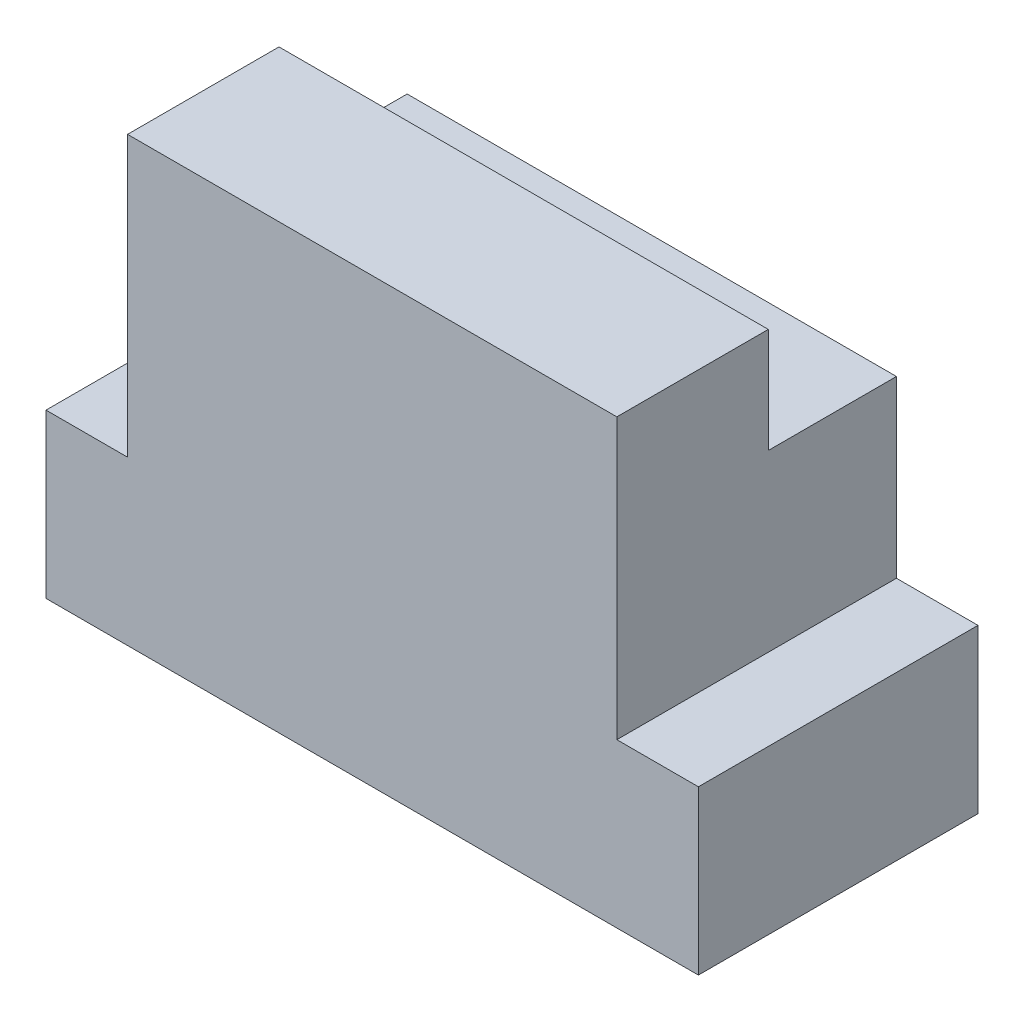
SolidWorks part; units mm, degrees
ref_plane "Front Plane" through (0, 0, 0) normal (0, 0, 1) x (1, 0, 0)
ref_plane "Top Plane" through (0, 0, 0) normal (0, 1, 0) x (1, 0, 0)
ref_plane "Right Plane" through (0, 0, 0) normal (1, 0, 0) x (0, 0, -1)
sketch "Sketch1" plane through (0, 0, 0) normal (0, 1, 0) x (1, 0, 0)
  line L1 (-28, -12) -> (28, -12)
  line L2 (-28, -12) -> (-28, 12)
  line L3 (-28, 12) -> (28, 12)
  line L4 (28, -12) -> (28, 12)
  line L5 (-28, -12) -> (28, 12) construction
  line L6 (-28, 12) -> (28, -12) construction
  point P0 (0, 0)
  dimension "D1" = 56
  dimension "D2" = 24
extrude "Boss-Extrude1" add sketch "Sketch1" along normal blind 14
sketch "Sketch5" plane through (0, 14, 0) normal (0, 1, 0) x (1, 0, 0)
  line L0 (-21, -12) -> (21, -12)
  line L1 (-28, -12) -> (28, -12) construction
  line L2 (21, -12) -> (21, 1)
  line L3 (21, 1) -> (-21, 1)
  line L4 (0, -7.7) -> (0, 7.7) construction
  line L5 (-21, -12) -> (-21, 1)
  point P9 (0, 1)
  point P10 (0, -12)
  dimension "D1" = 21
  dimension "D2" = 13
extrude "Boss-Extrude4" add sketch "Sketch5" along normal blind 24
sketch "Sketch6" plane through (0, 14, 0) normal (0, 1, 0) x (1, 0, 0)
  line L0 (-21, 1) -> (-21, 12)
  line L1 (28, 12) -> (-28, 12) construction
  line L2 (-21, 12) -> (21, 12)
  line L3 (21, 12) -> (21, 1)
  line L4 (21, 1) -> (-21, 1)
extrude "Boss-Extrude5" add sketch "Sketch6" along normal blind 15
